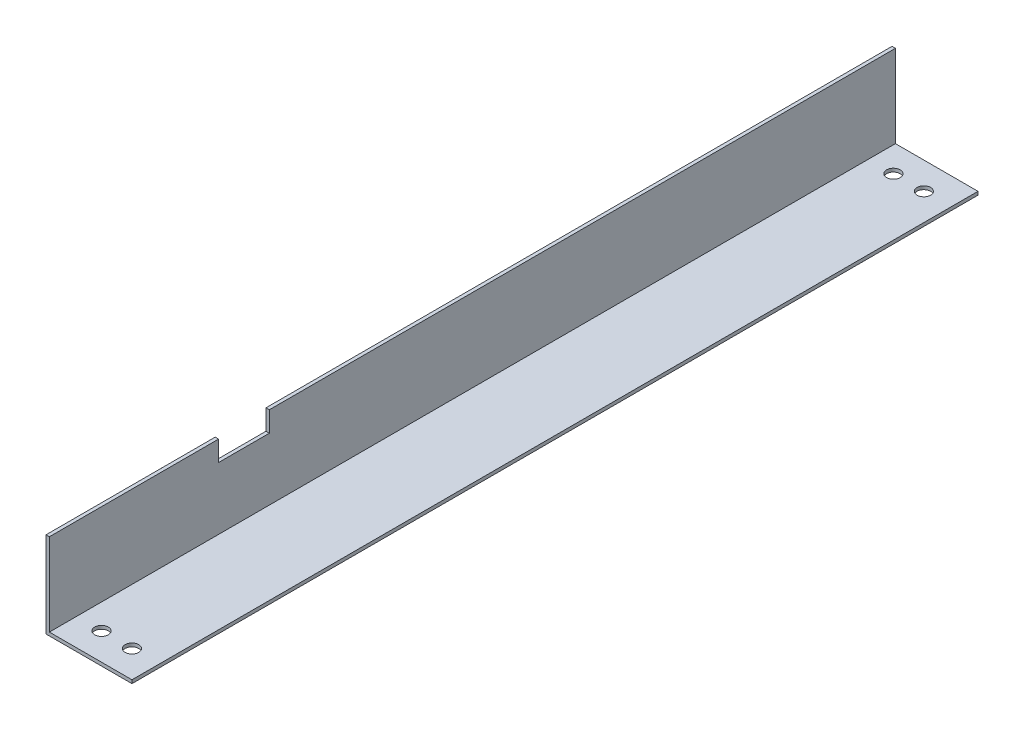
SolidWorks part; units mm, degrees
ref_plane "Front Plane" through (0, 0, 0) normal (0, 0, 1) x (1, 0, 0)
ref_plane "Top Plane" through (0, 0, 0) normal (0, 1, 0) x (1, 0, 0)
ref_plane "Right Plane" through (0, 0, 0) normal (1, 0, 0) x (0, 0, -1)
sketch "Sketch1" plane through (0, 0, 0) normal (0, 0, 1) x (1, 0, 0)
  line L0 (0, 0) -> (25.4, 0)
  line L1 (25.4, 0) -> (25.4, 1)
  line L2 (25.4, 1) -> (1, 1)
  line L3 (1, 1) -> (1, 25.4)
  line L4 (1, 25.4) -> (0, 25.4)
  line L5 (0, 25.4) -> (0, 0)
  dimension "D1" = 25.4
  dimension "D2" = 25.4
  dimension "D3" = 1
  dimension "D4" = 1
extrude "Boss-Extrude1" add sketch "Sketch1" against normal blind 250
sketch "Sketch2" plane through (0, 1, 0) normal (0, 1, 0) x (1, 0, 0)
  line L0 (25.4, 0) -> (1, 0) construction
  line L1 (25.4, 250) -> (25.4, 0) construction
  line L2 (25.4, 250) -> (1, 250) construction
  circle A0 centre (8.4, 8) radius 2
  circle A1 centre (17.4, 8) radius 2
  circle A2 centre (8.4, 242) radius 2
  circle A3 centre (17.4, 242) radius 2
  point P8 (0, 0)
  point P9 (0, 0)
  point P10 (0, 0)
  point P11 (0, 0)
  point P12 (0, 0)
  point P13 (0, 0)
  point P14 (0, 0)
  point P15 (19.7962, 243.6188)
  point P16 (5.7395, 243.6188)
  point P17 (7.4658, 243.6188)
  point P18 (18.5631, 6.8744)
  point P19 (17.8976, 242.1811)
  point P20 (8.6693, 242.1811)
  point P21 (17.8138, 8.15)
  point P22 (7.5482, 8.6944)
  dimension "D1" = 4
  dimension "D2" = 4
  dimension "D3" = 4
  dimension "D4" = 4
  dimension "D5" = 8
  dimension "D6" = 8
  dimension "D7" = 9
  dimension "D8" = 8
extrude "Cut-Extrude1" cut sketch "Sketch2" against normal up to surface (1 mm away) up to face at (12.7, 0, -125)
sketch "Sketch3" plane through (1, 0, 0) normal (1, 0, 0) x (0, 0, -1)
  line L0 (250, 25.4) -> (0, 25.4) construction
  line L1 (50, 25.4) -> (65, 25.4)
  line L2 (50, 25.4) -> (50, 19.4)
  line L3 (50, 19.4) -> (65, 19.4)
  line L4 (65, 25.4) -> (65, 19.4)
  line L5 (0, 1) -> (0, 25.4) construction
  dimension "D1" = 50
  dimension "D2" = 15
  dimension "D3" = 6
extrude "Cut-Extrude2" cut sketch "Sketch3" against normal up to surface (1 mm away) up to face at (0, 12.7, -125)
